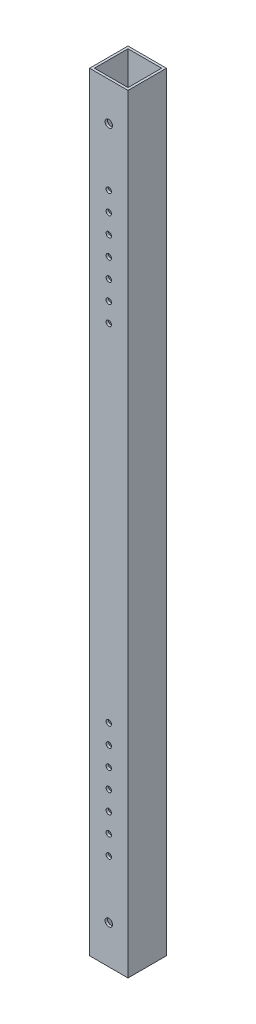
SolidWorks part; units mm, degrees
material "6061-T6 (SS)"
ref_plane "Front Plane" through (0, 0, 0) normal (0, 0, 1) x (1, 0, 0)
ref_plane "Top Plane" through (0, 0, 0) normal (0, 1, 0) x (1, 0, 0)
ref_plane "Right Plane" through (0, 0, 0) normal (1, 0, 0) x (0, 0, -1)
sketch "Sketch1" plane through (0, 0, 0) normal (0, 1, 0) x (1, 0, 0)
  line L0 (11.1125, 11.1125) -> (-11.1125, 11.1125)
  line L1 (12.7, -12.7) -> (-12.7, -12.7)
  line L2 (12.7, -12.7) -> (12.7, 12.7)
  line L3 (12.7, 12.7) -> (-12.7, 12.7)
  line L4 (-12.7, -12.7) -> (-12.7, 12.7)
  line L5 (12.7, -12.7) -> (-12.7, 12.7) construction
  line L6 (12.7, 12.7) -> (-12.7, -12.7) construction
  line L7 (-11.1125, -11.1125) -> (-11.1125, 11.1125)
  line L8 (11.1125, -11.1125) -> (-11.1125, -11.1125)
  line L9 (11.1125, -11.1125) -> (11.1125, 11.1125)
  point P0 (0, 0)
  dimension "D1" = 25.4
  dimension "D2" = 25.4
  dimension "D3" = 1.5875
extrude "Boss-Extrude1" add sketch "Sketch1" along normal mid plane 508
sketch "Sketch2" plane through (0, 0, -12.7) normal (0, 0, -1) x (-1, 0, 0)
  line L0 (-12.7, 254) -> (12.7, 254) construction
  line L1 (12.7, 254) -> (12.7, -254) construction
  line L2 (-12.7, -254) -> (12.7, -254) construction
  point P0 (0, 228.6)
  point P1 (0, -228.6)
  point P3 (0, 254)
  point P8 (0, -254)
  dimension "D1" = 25.4
  dimension "D2" = 12.7
  dimension "D3" = 25.4
  dimension "D4" = 12.7
hole_wizard "#10 (0.1935) Diameter Hole1" positions "Sketch4" profile "Sketch3" hole size "#10" standard "ANSI Inch"
sketch "Sketch4" plane through (0, 0, -12.7) normal (0, 0, -1) x (-1, 0, 0)
  point P0 (0, 228.6)
  point P3 (0, -228.6)
sketch "Sketch3" plane through (0, 228.6, -12.7) normal (1, 0, 0) x (0, 1, 0)
  line L0 (0, 0) -> (0, 52.2766)
  line L1 (0, 52.2766) -> (2.4574, 50.8)
  line L2 (2.4574, 50.8) -> (2.4574, 0)
  line L5 (2.4574, 0) -> (0, 0)
  line L10 (0, 52.2766) -> (-2.4575, 50.8) construction
  line L11 (0, -6.35) -> (0, 107.95) construction
  dimension "Hole Dia." = 4.9149
  dimension "Hole Depth" = 50.8
  dimension "Drill Angle" = 118
sketch "Sketch5" plane through (0, 0, 12.7) normal (0, 0, 1) x (1, 0, 0)
  line L1 (-12.7, 254) -> (12.7, 254) construction
  circle A0 centre (0, 190.5) radius 1.778
  circle A1 centre (0, 139.7) radius 1.778
  circle A2 centre (0, 177.8) radius 1.778
  circle A3 centre (0, 165.1) radius 1.778
  circle A4 centre (0, 152.4) radius 1.778
  circle A5 centre (0, 127) radius 1.778
  circle A6 centre (0, 114.3) radius 1.778
  dimension "D1" = 63.5
  dimension "D3" = 7
extrude "Cut-Extrude1" cut sketch "Sketch5" against normal through all
mirror "Mirror1" about plane through (0, 0, 0) normal (0, 1, 0) of "Cut-Extrude1"
